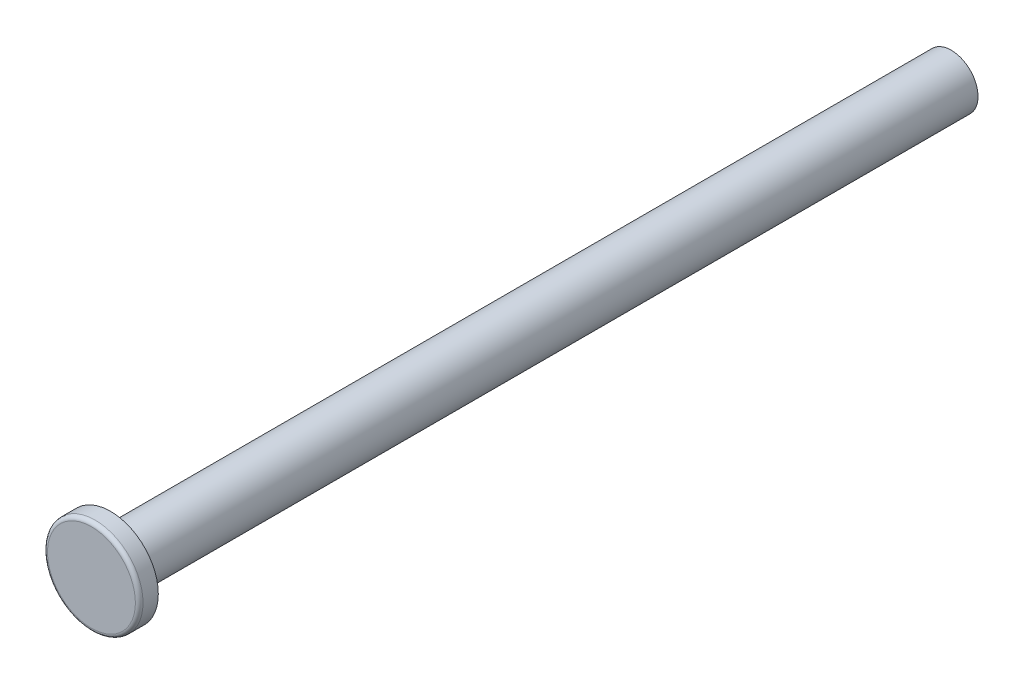
SolidWorks part; units mm, degrees
ref_plane "Front Plane" through (0, 0, 0) normal (0, 0, 1) x (1, 0, 0)
ref_plane "Top Plane" through (0, 0, 0) normal (0, 1, 0) x (1, 0, 0)
ref_plane "Right Plane" through (0, 0, 0) normal (1, 0, 0) x (0, 0, -1)
sketch "Sketch1" plane through (0, 0, 0) normal (0, 0, 1) x (1, 0, 0)
  circle A0 centre (0, 0) radius 7
  dimension "D1" = 14
extrude "Boss-Extrude1" add sketch "Sketch1" along normal mid plane 220
sketch "Sketch2" plane through (0, 0, 110) normal (0, 0, 1) x (1, 0, 0)
  circle A0 centre (0, 0) radius 12.5
  dimension "D1" = 25
extrude "Boss-Extrude2" add sketch "Sketch2" along normal blind 5 contours A0
fillet "Fillet1" radius 1 1 edges at (12.5, 0, 115)
